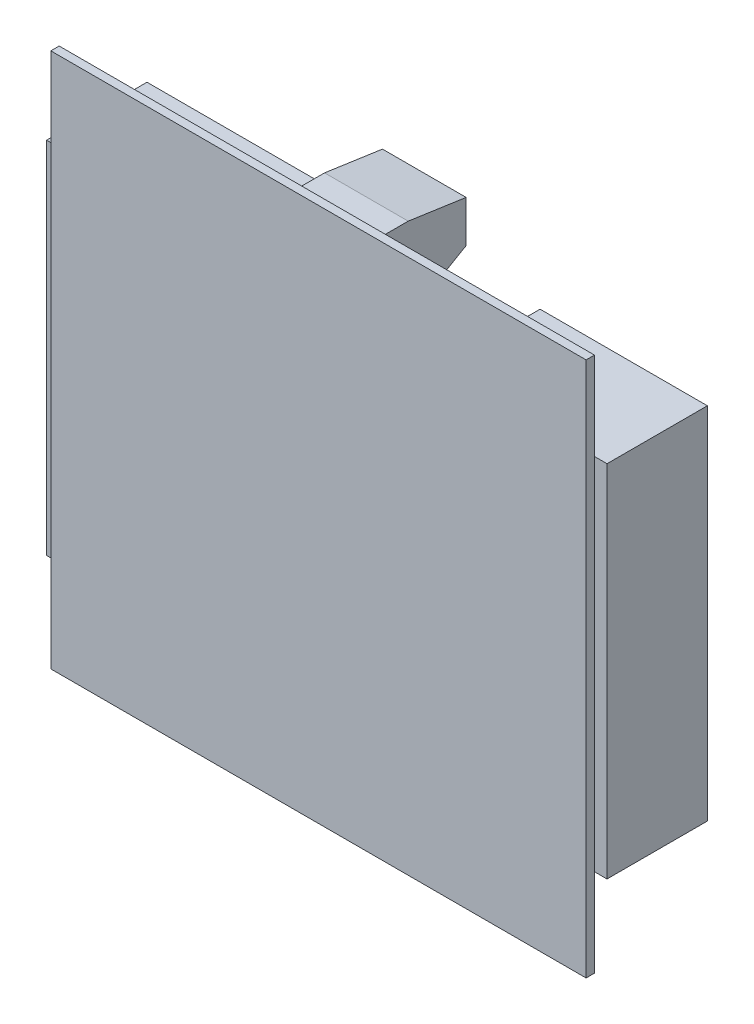
SolidWorks part; units mm, degrees
ref_plane "Front Plane" through (0, 0, 0) normal (0, 0, 1) x (1, 0, 0)
ref_plane "Top Plane" through (0, 0, 0) normal (0, 1, 0) x (1, 0, 0)
ref_plane "Right Plane" through (0, 0, 0) normal (1, 0, 0) x (0, 0, -1)
ref_plane "Plane1" through (0, 0, 0) normal (0, 0, 1) x (1, 0, 0)
ref_plane "Plane2" through (0, 0, 0) normal (0, 1, 0) x (1, 0, 0)
ref_plane "Plane3" through (0, 0, 0) normal (1, 0, 0) x (0, 0, -1)
sketch "Sketch2" plane through (0, 0, 0) normal (0, 0, 1) x (1, 0, 0)
  line L1 (0, 0) -> (64, 0)
  line L2 (0, 0) -> (0, 64)
  line L3 (0, 64) -> (64, 64)
  line L4 (64, 0) -> (64, 64)
  dimension "D1" = 64
  dimension "6" = 64
extrude "Boss-Extrude1" add sketch "Sketch2" along normal blind 1
sketch "Sketch3" plane through (0, 0, 0) normal (0, 0, 1) x (1, 0, 0)
  line L1 (-1.5, 53.5) -> (18.5, 53.5)
  line L2 (-1.5, 53.5) -> (-1.5, 10.5)
  line L3 (-1.5, 10.5) -> (18.5, 10.5)
  line L4 (18.5, 53.5) -> (18.5, 10.5)
  line L5 (64, 64) -> (0, 64) construction
  line L7 (32, 64) -> (32, 0) construction
  line L8 (0.55, 0) -> (-0.55, 0) construction
  line L13 (0, -0.55) -> (0, 0.55) construction
  line L15 (65.5, 10.5) -> (45.5, 10.5)
  line L16 (45.5, 53.5) -> (45.5, 10.5)
  line L17 (65.5, 53.5) -> (45.5, 53.5)
  line L18 (65.5, 53.5) -> (65.5, 10.5)
  dimension "D1" = 10.5
  dimension "D2" = 1.5
  dimension "D3" = 43
  dimension "D4" = 20
extrude "Boss-Extrude2" add sketch "Sketch3" against normal blind 12
ref_plane "Plane4" through (27, 0, 0) normal (1, 0, 0) x (0, 0, -1)
sketch "Sketch5" plane through (27, 0, 0) normal (1, 0, 0) x (0, 0, -1)
  line L0 (11.6545, 3.0021) -> (4.73, 2)
  line L1 (0, 35.2) -> (0, -35.2) construction
  line L2 (0, 12) -> (4.73, 12)
  line L3 (4.73, 12) -> (11.6545, 8.0021)
  line L4 (11.6545, 8.0021) -> (11.6545, 3.0021)
  line L5 (4.73, 2) -> (0, 2)
  line L6 (0, 2) -> (0, 12)
  line L7 (7.15, 0) -> (-7.15, 0) construction
  line L8 (-1, 32) -> (18.2115, 32) construction
  line L9 (-1, 64) -> (-1, 0) construction
  line L10 (-1, 64) -> (0, 64) construction
  line L11 (0, 62) -> (0, 52)
  line L12 (4.73, 62) -> (0, 62)
  line L13 (11.6545, 60.9979) -> (4.73, 62)
  line L14 (11.6545, 55.9979) -> (11.6545, 60.9979)
  line L15 (0, 52) -> (4.73, 52)
  line L16 (4.73, 52) -> (11.6545, 55.9979)
  dimension "D1" = 2
  dimension "D2" = 10
  dimension "D3" = 5
  dimension "D4" = 150
  dimension "D5" = 32
extrude "Boss-Extrude3" add sketch "Sketch5" along normal blind 10
